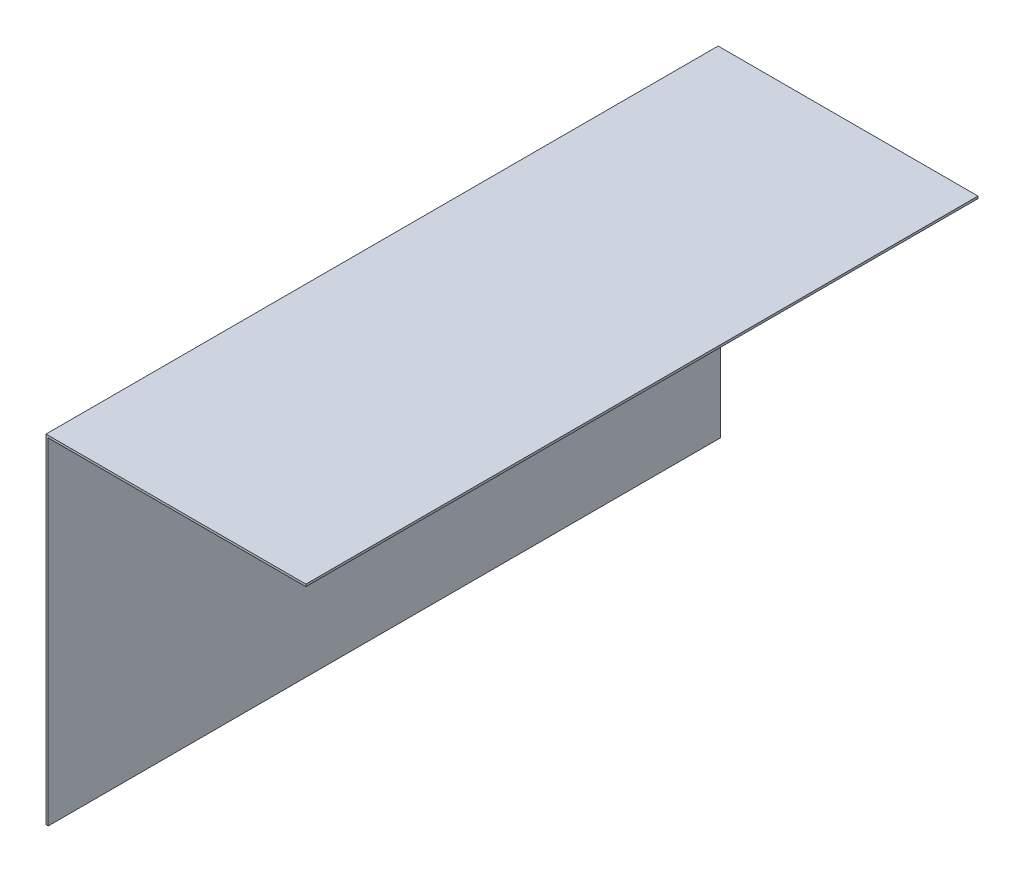
SolidWorks part; units mm, degrees
material "ABS"
ref_plane "Alzado" through (0, 0, 0) normal (0, 0, 1) x (1, 0, 0)
ref_plane "Planta" through (0, 0, 0) normal (0, 1, 0) x (1, 0, 0)
ref_plane "Vista lateral" through (0, 0, 0) normal (1, 0, 0) x (0, 0, -1)
sketch "Croquis1" plane through (0, 0, 0) normal (0, 0, 1) x (1, 0, 0)
  line L0 (0, 0) -> (230, 0)
  line L1 (0, 0) -> (0, -300)
  line L2 (-2, 2) -> (230, 2)
  line L3 (-2, 2) -> (-2, -300)
  line L4 (230, 0) -> (230, 2)
  line L5 (0, -300) -> (-2, -300)
  dimension "D1" = 230
  dimension "D2" = 300
  dimension "D3" = 2
extrude "Saliente-Extruir1" add sketch "Croquis1" along normal blind 600
